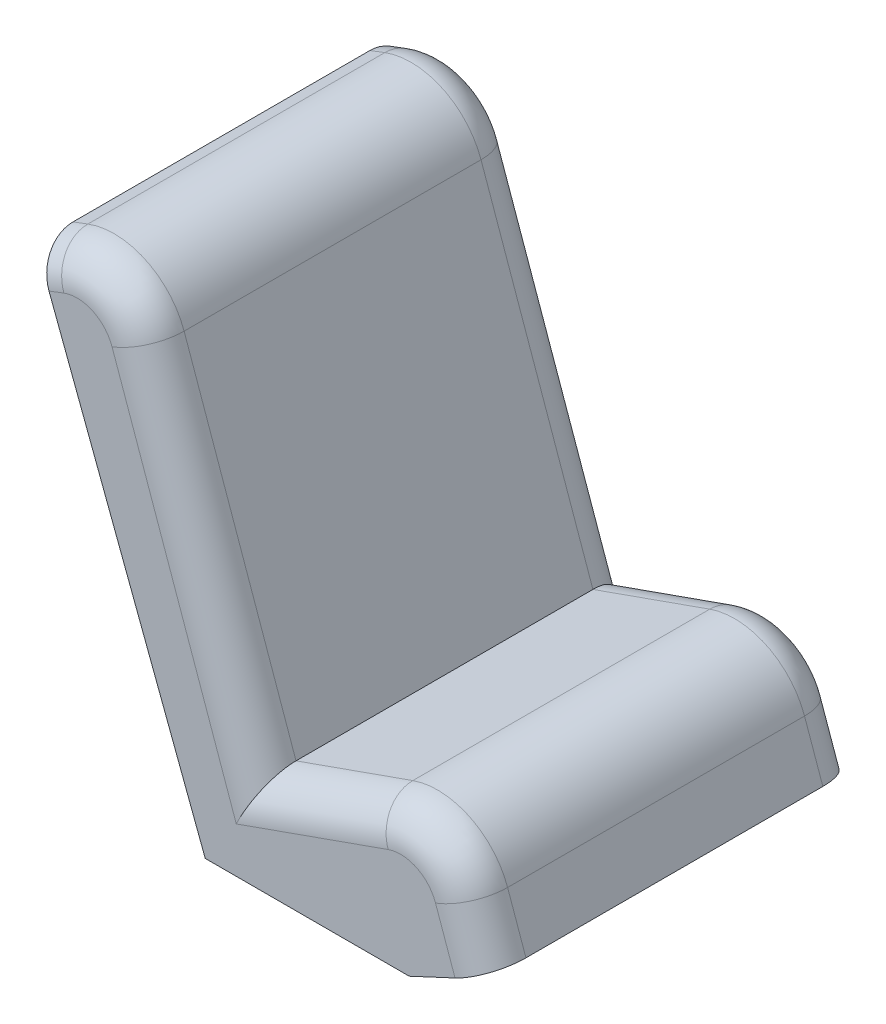
SolidWorks part; units mm, degrees
ref_plane "Ön Düzlem" through (0, 0, 0) normal (0, 0, 1) x (1, 0, 0)
ref_plane "Üst Düzlem" through (0, 0, 0) normal (0, 1, 0) x (1, 0, 0)
ref_plane "Sağ Düzlem" through (0, 0, 0) normal (1, 0, 0) x (0, 0, -1)
sketch "Çizim1" plane through (0, 0, 0) normal (0, 0, 1) x (1, 0, 0)
  line L0 (-45.3724, 120) -> (0, 0)
  line L1 (0, 0) -> (57.1, 0)
  line L2 (57.1, 0) -> (78.5451, 10)
  line L3 (78.5451, 10) -> (73.6047, 23.9605)
  line L4 (48.0782, 36.1426) -> (16.5917, 25)
  line L5 (16.5917, 25) -> (-13.5561, 110.1913)
  line L6 (-39.4837, 122.2265) -> (-45.3724, 120)
  arc A0 (73.6047, 23.9605) -> (48.0782, 36.1426) centre (54.7504, 17.2883) ccw
  arc A1 (-13.5561, 110.1913) -> (-39.4837, 122.2265) centre (-32.4103, 103.5191) ccw
  point P12 (-20.3724, 129.4526)
  point P13 (76.0749, 16.9803)
  dimension "D5" = 20
  dimension "D9" = 20
  dimension "D1" = 120
  dimension "D2" = 57.1
  dimension "D3" = 10
  dimension "D4" = 25
  dimension "D6" = 53.4
  dimension "D7" = 25
  dimension "D8" = 25
  dimension "D10" = 16.5917
extrude "Yükseklik-Ekstrüzyon1" add sketch "Çizim1" along normal mid plane 100
sketch "Çizim2" plane through (0, 0, 0) normal (0, -1, 0) x (1, 0, 0)
  line L0 (0, 50) -> (0, -50) construction
  circle A0 centre (30, 0) radius 7.5
  dimension "D1" = 15
  dimension "D2" = 30
extrude "Yükseklik-Ekstrüzyon2" add sketch "Çizim2" along normal blind 10
fillet "Radyus1" radius 10 12 edges at (76.0749, 16.9803, -50) (63.3644, 35.3383, -50) (76.0749, 16.9803, 50) (63.3644, 35.3383, 50) (-42.428, 121.1133, -50) (-23.9896, 121.66, -50) (-42.428, 121.1133, 50) (-23.9896, 121.66, 50) (32.335, 30.5713, -50) (32.335, 30.5713, 50) (1.5178, 67.5957, -50) (1.5178, 67.5957, 50)
chamfer "Pah1" distance 2 angle 45 5 edges at (-20.9178, 55.3231, -50) (-44.3365, 117.2604, -47.0711) (-45.3724, 120, 0) (-44.3365, 117.2604, 47.0711) (-20.9178, 55.3231, 50)
